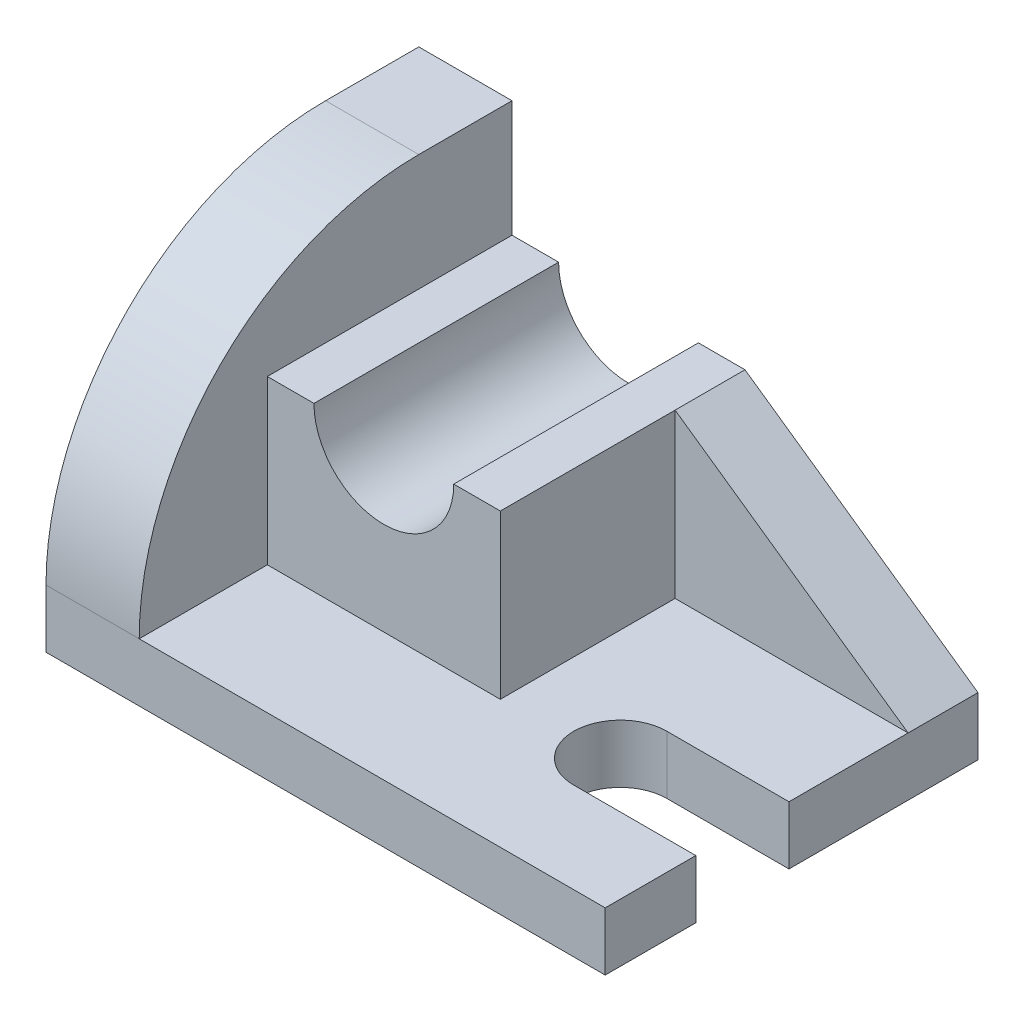
SolidWorks part; units mm, degrees
ref_plane "Front Plane" through (0, 0, 0) normal (0, 0, 1) x (1, 0, 0)
ref_plane "Top Plane" through (0, 0, 0) normal (0, 1, 0) x (1, 0, 0)
ref_plane "Right Plane" through (0, 0, 0) normal (1, 0, 0) x (0, 0, -1)
sketch "Sketch3" plane through (0, 0, 0) normal (0, 1, 0) x (1, 0, 0)
  line L0 (0, 0) -> (0, 64)
  line L1 (0, 64) -> (96, 64)
  line L2 (96, 64) -> (96, 0)
  line L3 (96, 0) -> (0, 0)
extrude "Boss-Extrude1" add sketch "Sketch3" along normal blind 10
sketch "Sketch4" plane through (0, 10, 0) normal (0, 1, 0) x (1, 0, 0)
  line L0 (96, 15.5509) -> (96, 31.5509)
  line L1 (96, 0) -> (96, 64) construction
  line L2 (96, 15.5509) -> (75.0433, 15.5509)
  line L3 (96, 31.5509) -> (75.0433, 31.5509)
  arc A0 (75.0433, 31.5509) -> (75.0433, 15.5509) centre (75.0433, 23.5509) ccw
extrude "Cut-Extrude1" cut sketch "Sketch4" against normal blind 10
sketch "Sketch5" plane through (0, 0, 0) normal (0, 0, 1) x (1, 0, 0)
  line L0 (0, 10) -> (0, 58)
  line L1 (0, 58) -> (16, 58)
  line L2 (16, 58) -> (16, 10)
  line L3 (96, 10) -> (0, 10) construction
  line L4 (16, 10) -> (0, 10)
  point P4 (0, 0)
extrude "Boss-Extrude2" add sketch "Sketch5" against normal through all
sketch "Sketch6" plane through (0, 0, 0) normal (1, 0, 0) x (0, 0, -1)
  line L0 (0, 58) -> (0, 10)
  line L1 (64, 10) -> (0, 10) construction
  line L4 (48, 58) -> (0, 58)
  arc A1 (48, 58) -> (0, 10) centre (48, 10) ccw
extrude "Cut-Extrude5" cut sketch "Sketch6" along normal up to next and the other way through all contours L0 A1 L4
sketch "Sketch8" plane through (0, 0, 0) normal (0, 0, 1) x (1, 0, 0)
  line L0 (16, 10) -> (16, 38)
  line L1 (16, 10) -> (16, 58) construction
  line L2 (16, 38) -> (24, 38)
  line L3 (16, 10) -> (56, 10)
  line L4 (96, 10) -> (16, 10) construction
  line L5 (56, 10) -> (56, 38)
  line L6 (56, 38) -> (48, 38)
  arc A1 (24, 38) -> (48, 38) centre (36, 38) ccw
extrude "Boss-Extrude3" add sketch "Sketch8" along normal blind 42 from surface at -64 starting at face at (37.3333, 22.6667, -64)
sketch "Sketch10" plane through (0, 0, -64) normal (0, 0, -1) x (-1, 0, 0)
  line L0 (-56, 38) -> (-96, 10)
  line L1 (-96, 10) -> (-56, 10)
  line L2 (-56, 10) -> (-56, 38)
extrude "Boss-Extrude4" add sketch "Sketch10" against normal blind 12
